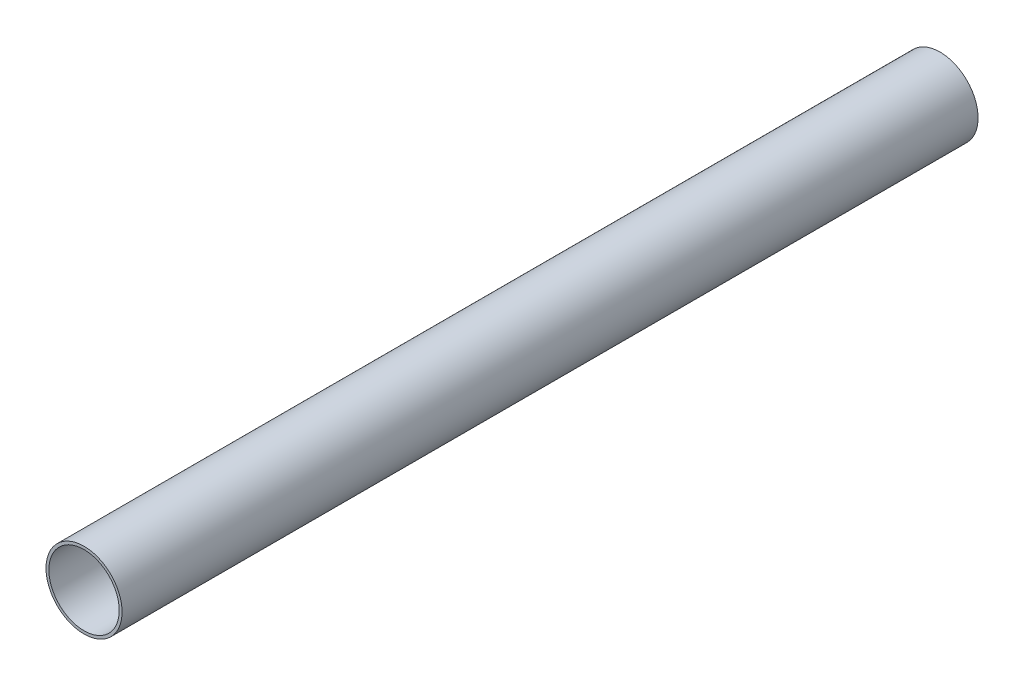
SolidWorks part; units mm, degrees
ref_plane "Front Plane" through (0, 0, 0) normal (0, 0, 1) x (1, 0, 0)
ref_plane "Top Plane" through (0, 0, 0) normal (0, 1, 0) x (1, 0, 0)
ref_plane "Right Plane" through (0, 0, 0) normal (1, 0, 0) x (0, 0, -1)
sketch "Sketch1" plane through (0, 0, 0) normal (0, 0, 1) x (1, 0, 0)
  circle A0 centre (0, 0) radius 8
  circle A1 centre (0, 0) radius 7.4
  dimension "D1" = 16
  dimension "D2" = 0.6
extrude "Boss-Extrude1" add sketch "Sketch1" along normal blind 180
